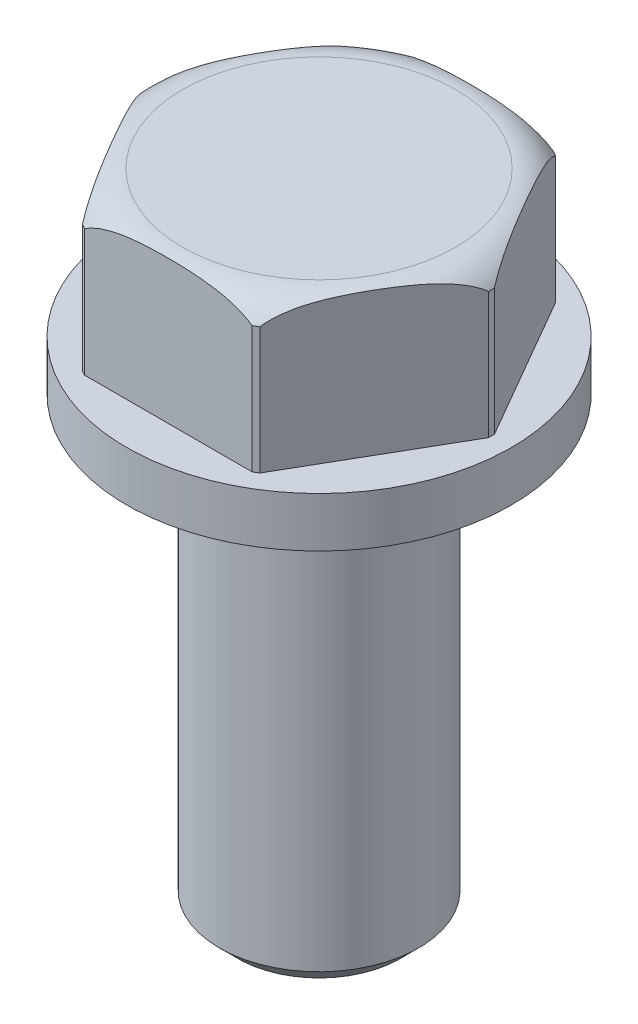
SolidWorks part; units mm, degrees
ref_plane "Alzado" through (0, 0, 0) normal (0, 0, 1) x (1, 0, 0)
ref_plane "Planta" through (0, 0, 0) normal (0, 1, 0) x (1, 0, 0)
ref_plane "Vista lateral" through (0, 0, 0) normal (1, 0, 0) x (0, 0, -1)
sketch "Croquis1" plane through (0, 0, 0) normal (0, 0, 1) x (1, 0, 0)
  line L0 (0, 0) -> (0, 40.9956) construction
  line L1 (0, 40.9956) -> (10.9855, 40.9956)
  line L2 (10.9855, 40.9956) -> (10.9855, 31.7246)
  line L3 (10.9855, 31.7246) -> (12.2555, 31.7246)
  line L4 (12.2555, 31.7246) -> (12.2555, 28.5496)
  line L5 (12.2555, 28.5496) -> (6.35, 28.5496)
  line L6 (6.35, 28.5496) -> (6.35, 0)
  line L7 (6.35, 0) -> (0, 0)
  line L8 (0, 0) -> (0, 40.9956) construction
  line L9 (0, 0) -> (0, 40.9956)
  dimension "D1" = 12.7
  dimension "D2" = 21.971
  dimension "D3" = 24.511
  dimension "D4" = 40.9956
  dimension "D5" = 9.271
  dimension "D6" = 3.175
revolve "Revolución1" add sketch "Croquis1" angle 360 about L9
sketch "Croquis2" plane through (0, 40.9956, 0) normal (0, 1, 0) x (1, 0, 0)
  line L1 (-5.334, 9.6036) -> (5.334, 9.6036)
  line L2 (-5.334, 9.6036) -> (-5.334, 14.6836)
  line L3 (-5.334, 14.6836) -> (5.334, 14.6836)
  line L4 (5.334, 9.6036) -> (5.334, 14.6836)
  circle A0 centre (0, 0) radius 10.9855 construction
  circle A1 centre (0, 0) radius 10.9855 construction
  dimension "D1" = 10.668
  dimension "D2" = 5.08
extrude "Cortar-Extruir1" cut sketch "Croquis2" against normal up to surface (9.271 mm away) up to face at (0, 31.7246, -10.9855)
pattern_circular "MatrizC1" count 6 over 360 about axis through (0, 0, 0) along (0, 1, 0) of "Cortar-Extruir1"
sketch "Croquis3" plane through (0, 0, 0) normal (0, 0, 1) x (1, 0, 0)
  line L0 (11.176, 39.4716) -> (11.176, 40.9956)
  line L1 (11.176, 40.9956) -> (8.6995, 40.9956)
  line L2 (10.984, 40.9956) -> (5.65, 40.9956) construction
  line L3 (0, 31.7246) -> (0, 47.5384) construction
  line L4 (-5.334, 31.7246) -> (5.334, 31.7246) construction
  arc A0 (8.6995, 40.9956) -> (11.176, 39.4716) centre (8.6995, 38.2214) cw
  dimension "D1" = 22.352
  dimension "D2" = 17.399
  dimension "D3" = 1.524
revolve "Cortar-Revolución1" cut sketch "Croquis3" angle 360 about L3
chamfer "Chaflán1" distance 1.1633 angle 45 1 edges at (0, 0, -6.35)
